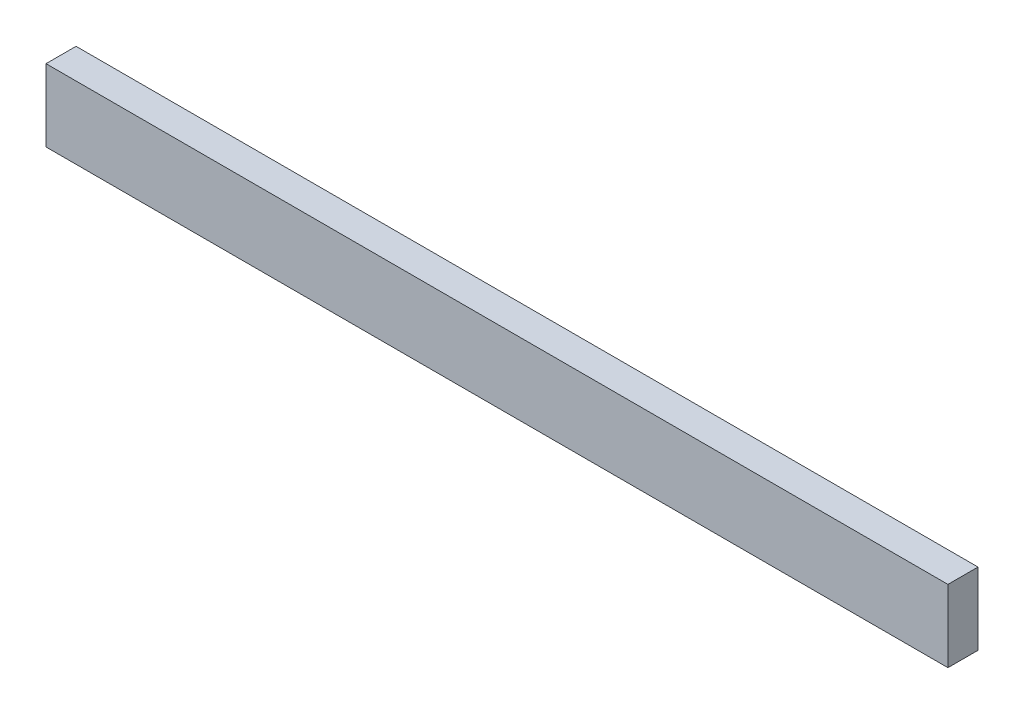
SolidWorks part; units mm, degrees
ref_plane "Plan de face" through (0, 0, 0) normal (0, 0, 1) x (1, 0, 0)
ref_plane "Plan de dessus" through (0, 0, 0) normal (0, 1, 0) x (1, 0, 0)
ref_plane "Plan de droite" through (0, 0, 0) normal (1, 0, 0) x (0, 0, -1)
sketch "Esquisse1" plane through (0, 0, 0) normal (0, 0, 1) x (1, 0, 0)
  line L1 (0, 0) -> (750, 0)
  line L2 (0, 0) -> (0, 60)
  line L3 (0, 60) -> (750, 60)
  line L4 (750, 0) -> (750, 60)
  dimension "D1" = 60
  dimension "D2" = 750
extrude "Boss.-Extru.1" add sketch "Esquisse1" along normal blind 25
